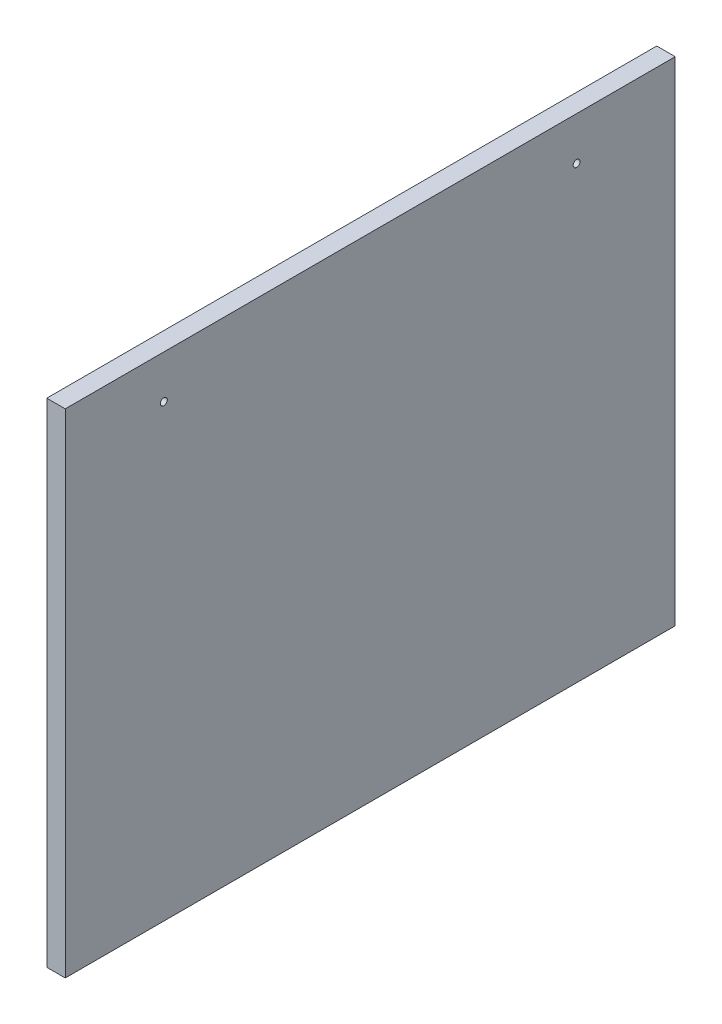
SolidWorks part; units mm, degrees
material "Pine"
ref_plane "Front Plane" through (0, 0, 0) normal (0, 0, 1) x (1, 0, 0)
ref_plane "Top Plane" through (0, 0, 0) normal (0, 1, 0) x (1, 0, 0)
ref_plane "Right Plane" through (0, 0, 0) normal (1, 0, 0) x (0, 0, -1)
sketch "Sketch1" plane through (0, 0, 0) normal (1, 0, 0) x (0, 0, -1)
  line L0 (0, 0) -> (628.65, 0)
  line L1 (0, 0) -> (0, 508)
  line L2 (628.65, 0) -> (628.65, 508)
  line L3 (0, 508) -> (628.65, 508)
  circle A0 centre (101.6, 463.55) radius 3.5719
  circle A1 centre (527.05, 463.55) radius 3.5719
  dimension "D7" = 7.1437
  dimension "D8" = 7.1437
  dimension "D1" = 508
  dimension "D2" = 628.65
  dimension "D3" = 44.45
  dimension "D4" = 44.45
  dimension "D5" = 101.6
  dimension "D6" = 101.6
extrude "Boss-Extrude1" add sketch "Sketch1" along normal blind 19.05
